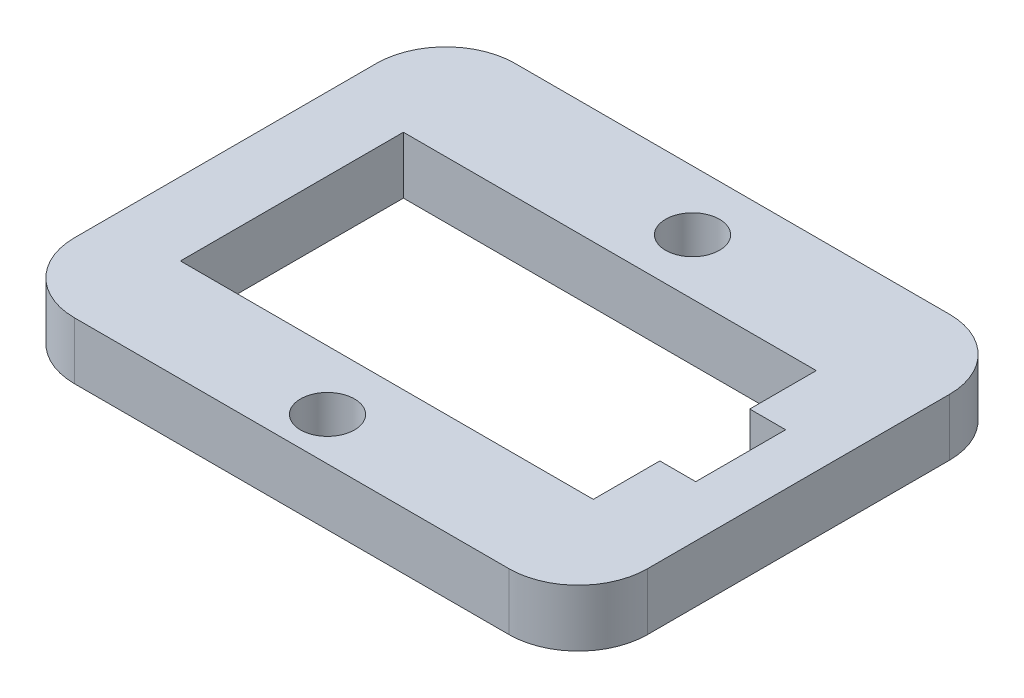
SolidWorks part; units mm, degrees
ref_plane "Front Plane" through (0, 0, 0) normal (0, 0, 1) x (1, 0, 0)
ref_plane "Top Plane" through (0, 0, 0) normal (0, 1, 0) x (1, 0, 0)
ref_plane "Right Plane" through (0, 0, 0) normal (1, 0, 0) x (0, 0, -1)
sketch "Sketch1" plane through (0, 0, 0) normal (0, 1, 0) x (1, 0, 0)
  line L0 (-2.4168, 9.3387) -> (-25.3759, 9.3387)
  line L1 (-25.3759, 9.3387) -> (-25.3759, -3.0616)
  line L2 (-25.3759, -3.0616) -> (-2.4168, -3.0616)
  line L3 (-2.4168, -3.0616) -> (-2.4168, 0.6385)
  line L4 (-2.4168, 0.6385) -> (-0.4201, 0.6385)
  line L5 (-0.4201, 0.6385) -> (-0.4201, 5.6386)
  line L6 (-0.4201, 5.6386) -> (-2.4168, 5.6386)
  line L7 (-2.4168, 5.6386) -> (-2.4168, 9.3387)
  line L8 (-1.4321, 15.7561) -> (-25.5836, 15.7561)
  line L9 (-29.4395, 11.9002) -> (-29.4395, -4.8819)
  line L10 (-25.5766, -8.7447) -> (-1.4252, -8.7447)
  line L11 (2.4307, -4.8889) -> (2.4307, 11.8933)
  arc A0 (-25.5836, 15.7561) -> (-29.4395, 11.9002) centre (-25.5836, 11.9002) ccw
  arc A1 (-29.4395, -4.8819) -> (-25.5766, -8.7447) centre (-25.5766, -4.8819) ccw
  arc A2 (-1.4252, -8.7447) -> (2.4307, -4.8889) centre (-1.4252, -4.8889) ccw
  arc A3 (2.4307, 11.8933) -> (-1.4321, 15.7561) centre (-1.4321, 11.8933) ccw
  circle A4 centre (-12.3988, 12.4389) radius 1.4986
  circle A5 centre (-13.8964, -6.3618) radius 1.4986
  point P26 (-12.3988, 12.4389)
  point P27 (-13.8964, -6.3618)
  dimension "D1" = 2.9972
extrude "Boss-Extrude1" add sketch "Sketch1" along normal blind 3.175
